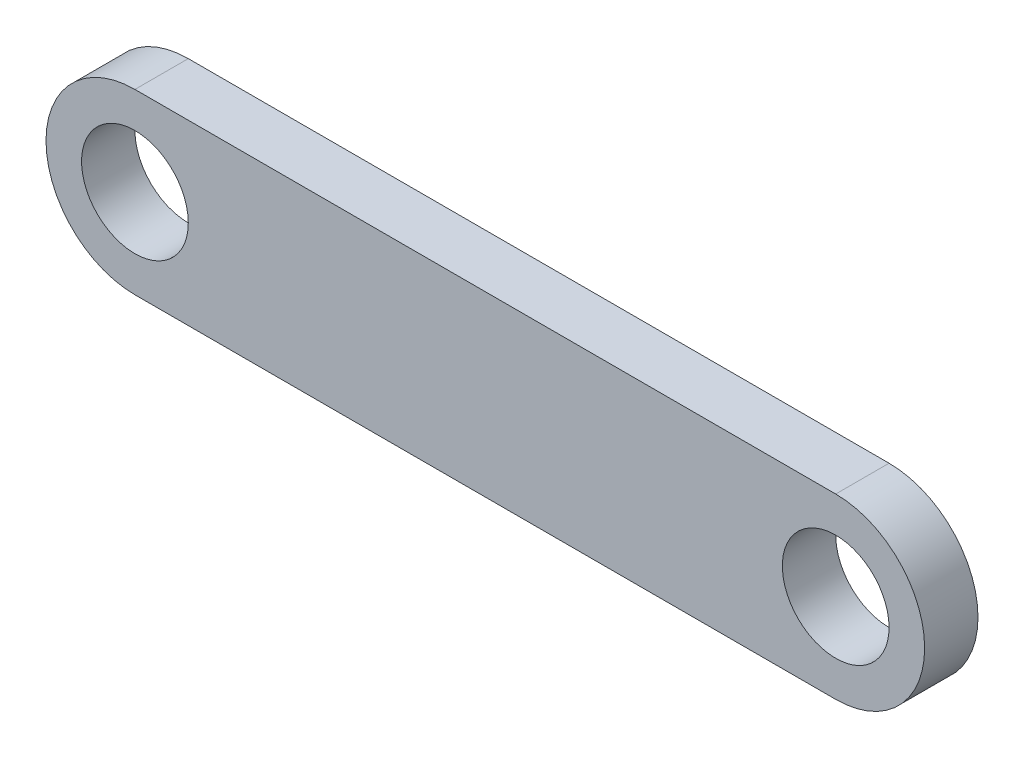
SolidWorks part; units mm, degrees
ref_plane "正面" through (0, 0, 0) normal (0, 0, 1) x (1, 0, 0)
ref_plane "平面" through (0, 0, 0) normal (0, 1, 0) x (1, 0, 0)
ref_plane "右側面" through (0, 0, 0) normal (1, 0, 0) x (0, 0, -1)
sketch "ｽｹｯﾁ1" plane through (0, 0, 0) normal (0, 0, 1) x (1, 0, 0)
  line L0 (-19.7, 0) -> (19.7, 0) construction
  line L1 (-19.7, 5) -> (19.7, 5)
  line L2 (-19.7, -5) -> (19.7, -5)
  arc A0 (-19.7, 5) -> (-19.7, -5) centre (-19.7, 0) ccw
  arc A1 (19.7, -5) -> (19.7, 5) centre (19.7, 0) ccw
  circle A2 centre (-19.7, 0) radius 3
  circle A3 centre (19.7, 0) radius 3
  point P2 (0, 0)
  dimension "D1" = 6
  dimension "D3" = 5
  dimension "D2" = 39.4
extrude "ﾎﾞｽ - 押し出し1" add sketch "ｽｹｯﾁ1" along normal blind 3
